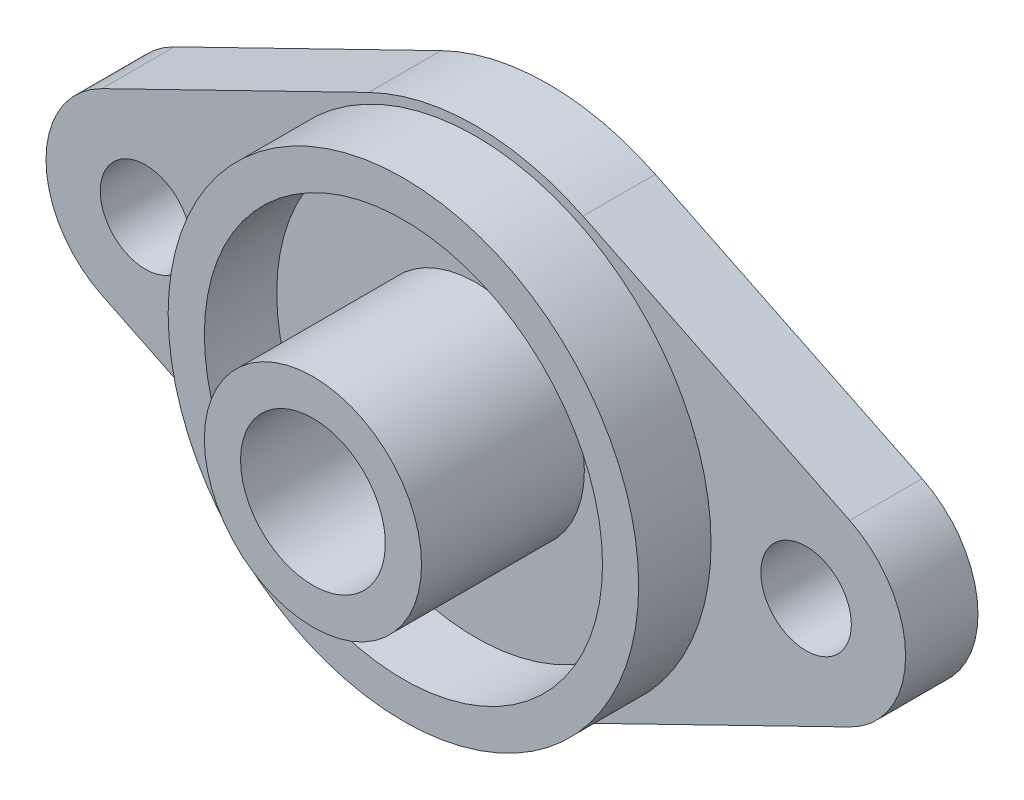
SolidWorks part; units mm, degrees
ref_plane "Front Plane" through (0, 0, 0) normal (0, 0, 1) x (1, 0, 0)
ref_plane "Top Plane" through (0, 0, 0) normal (0, 1, 0) x (1, 0, 0)
ref_plane "Right Plane" through (0, 0, 0) normal (1, 0, 0) x (0, 0, -1)
sketch "Sketch1" plane through (0, 0, 0) normal (0, 0, 1) x (1, 0, 0)
  line L0 (-18.25, 0) -> (45.953, 0) construction
  line L1 (0, 25.7609) -> (0, -36.9369) construction
  line L2 (-20.661, 4.9434) -> (-5.9178, 12.1338)
  line L3 (-20.661, -4.9434) -> (-5.9178, -12.1338)
  line L4 (20.661, -4.9434) -> (5.9178, -12.1338)
  line L5 (20.661, 4.9434) -> (5.9178, 12.1338)
  arc A0 (-5.9178, -12.1338) -> (5.9178, -12.1338) centre (0, 0) ccw
  arc A1 (-20.661, 4.9434) -> (-20.661, -4.9434) centre (-18.25, 0) ccw
  arc A2 (20.661, 4.9434) -> (20.661, -4.9434) centre (18.25, 0) cw
  circle A3 centre (0, 0) radius 13
  arc A4 (5.9178, 12.1338) -> (-5.9178, 12.1338) centre (0, 0) ccw
  circle A5 centre (0, 0) radius 12
  circle A6 centre (0, 0) radius 4
  circle A7 centre (0, 0) radius 5
  circle A8 centre (-18.25, 0) radius 2.5
  circle A9 centre (18.25, 0) radius 2.5
  dimension "D1" = 27
  dimension "D2" = 11
  dimension "D4" = 26
  dimension "D5" = 24
  dimension "D6" = 8
  dimension "D7" = 10
  dimension "D8" = 5
  dimension "D9" = 5
  dimension "D3" = 18.25
extrude "Boss-Extrude5" add sketch "Sketch1" along normal blind 4 contours L3 A0 L4 A2 L5 A4 L2 A1
sketch "Sketch5" plane through (0, 0, 0) normal (0, 1, 0) x (1, 0, 0)
  line L0 (0, 13.4338) -> (0, -19.6096) construction
  line L1 (4, -13) -> (6, -13)
  line L2 (6, -13) -> (6, -10.517)
  line L3 (13, -8) -> (11, -8)
  line L4 (13, -8) -> (13, -4)
  line L5 (20.661, -4) -> (5.9178, -4) construction
  line L6 (4, -13) -> (4, -4)
  line L7 (-5.9178, -4) -> (5.9178, -4) construction
  line L8 (6, -10.517) -> (6, -4)
  line L9 (11, -8) -> (11, -4)
  line L10 (20.661, 0) -> (5.9178, 0) construction
  line L11 (4, -4) -> (6, -4)
  line L12 (11, -4) -> (13, -4)
  dimension "D1" = 4
  dimension "D2" = 13
  dimension "D3" = 13
  dimension "D4" = 2
  dimension "D5" = 8
revolve "Revolve2" add sketch "Sketch5" angle 360 about L0
sketch "Sketch14" plane through (0, 0, 0) normal (0, 0, 1) x (1, 0, 0)
  line L0 (-24.4506, 0) -> (25.5533, 0) construction
  line L1 (0, 14.6109) -> (0, -15.9736) construction
  circle A0 centre (-18.25, 0) radius 2.5
  circle A1 centre (18.25, 0) radius 2.5
  point P3 (-18.25, 0)
  point P5 (18.25, 0)
  dimension "D1" = 5
  dimension "D2" = 5
  dimension "D3" = 18.25
  dimension "D4" = 18.25
hole_wizard "Ø5.0mm Dowel Hole1" positions "Sketch14" profile "Sketch15" hole size "Ø5.0" standard "ANSI Metric"
sketch "Sketch15" plane through (18.25, 0, 0) normal (1, 0, 0) x (0, 1, 0)
  line L0 (0, 0) -> (0, 11.6022)
  line L1 (0, 11.6022) -> (2.5, 10.1)
  line L2 (2.5, 10.1) -> (2.5, 0)
  line L5 (2.5, 0) -> (0, 0)
  line L10 (0, 11.6022) -> (-2.5, 10.1) construction
  line L11 (0, -6.35) -> (0, 107.95) construction
  dimension "Hole Dia." = 5
  dimension "Hole Depth" = 10.1
  dimension "Drill Angle" = 118
hole_wizard "Ø8.0mm Dowel Hole1" positions "Sketch16" profile "Sketch17" hole size "Ø8.0" standard "ANSI Metric"
sketch "Sketch16" plane through (0, 0, 4) normal (0, 0, 1) x (1, 0, 0)
  point P0 (0, 0)
sketch "Sketch17" plane through (0, 0, 4) normal (1, 0, 0) x (0, -1, 0)
  line L0 (0, 0) -> (0, 12.5034)
  line L1 (0, 12.5034) -> (4, 10.1)
  line L2 (4, 10.1) -> (4, 0)
  line L5 (4, 0) -> (0, 0)
  line L10 (0, 12.5034) -> (-4, 10.1) construction
  line L11 (0, -6.35) -> (0, 107.95) construction
  dimension "Hole Dia." = 8
  dimension "Hole Depth" = 10.1
  dimension "Drill Angle" = 118
